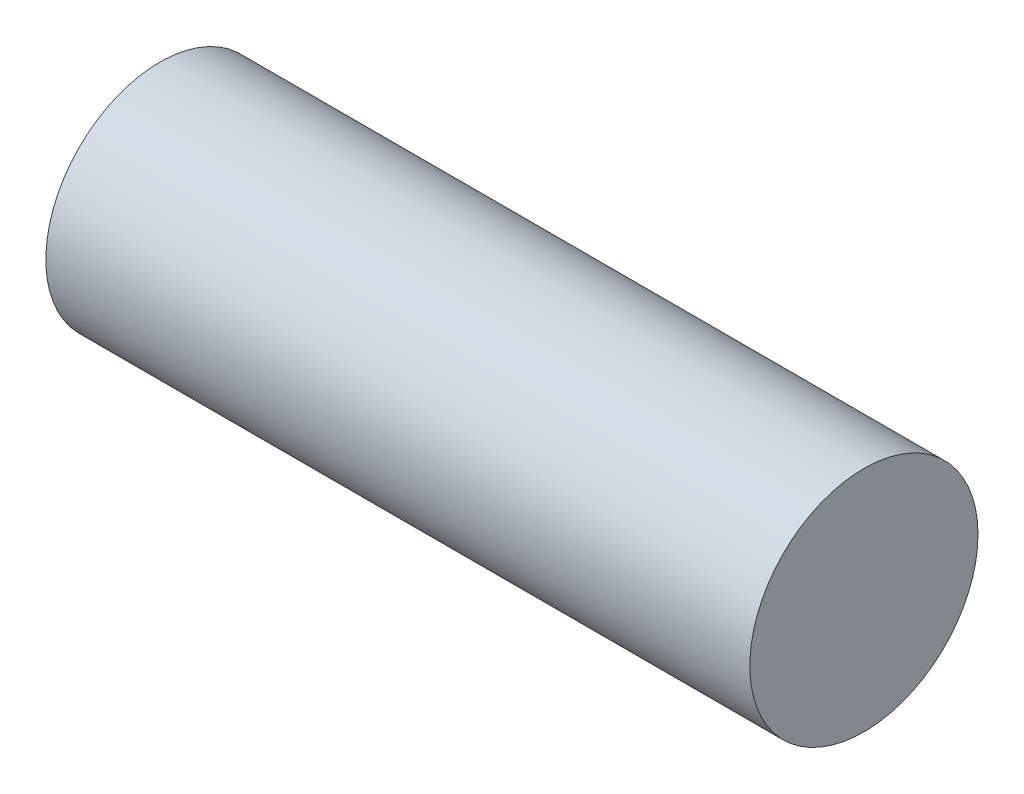
SolidWorks part; units mm, degrees
material "AISI Type A2 Tool Steel"
ref_plane "Front Plane" through (0, 0, 0) normal (1, 0, 0) x (0, 1, 0)
ref_plane "Top Plane" through (0, 0, 0) normal (0, 0, 1) x (0, 1, 0)
ref_plane "Right Plane" through (0, 0, 0) normal (0, 1, 0) x (-1, 0, 0)
sketch "Sketch1" plane through (0, 0, 0) normal (1, 0, 0) x (0, 1, 0)
  circle A0 centre (0, 0) radius 5.71
  dimension "D1" = 11.42
extrude "Boss-Extrude1" add sketch "Sketch1" along normal blind 35.23
